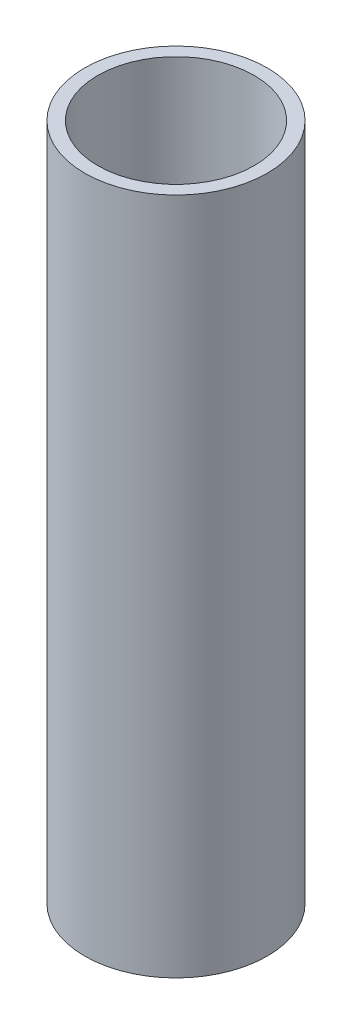
SolidWorks part; units mm, degrees
material "PVC Rigid"
ref_plane "Front Plane" through (0, 0, 0) normal (0, 0, 1) x (1, 0, 0)
ref_plane "Top Plane" through (0, 0, 0) normal (0, 1, 0) x (1, 0, 0)
ref_plane "Right Plane" through (0, 0, 0) normal (1, 0, 0) x (0, 0, -1)
sketch "Sketch1" plane through (0, 0, 0) normal (0, 1, 0) x (1, 0, 0)
  circle A0 centre (0, 0) radius 17.5
  dimension "D1" = 35
extrude "Boss-Extrude1" add sketch "Sketch1" along normal blind 130
sketch "Sketch2" plane through (0, 0, 0) normal (0, -1, 0) x (1, 0, 0)
  circle A0 centre (0, 0) radius 15
  dimension "D1" = 30
extrude "Cut-Extrude1" cut sketch "Sketch2" against normal through all
